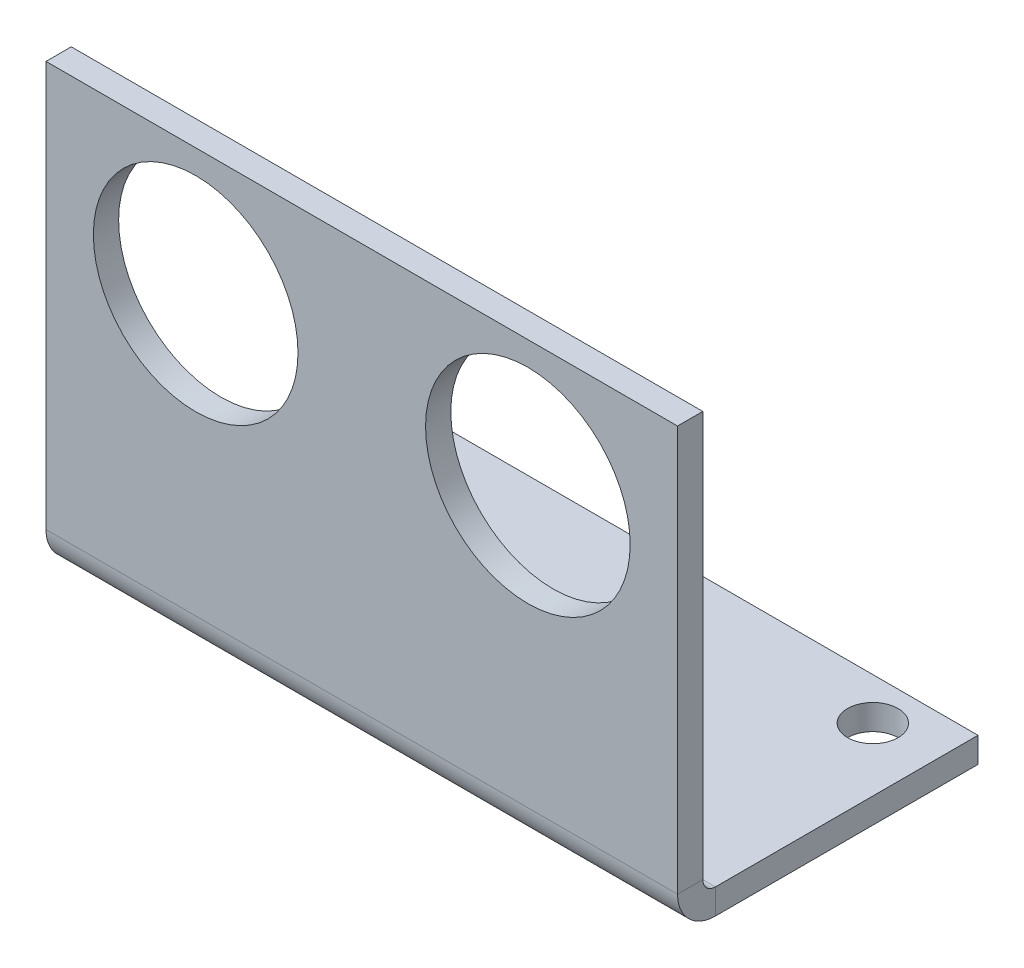
SolidWorks part; units mm, degrees
ref_plane "Front Plane" through (0, 0, 0) normal (0, 0, 1) x (1, 0, 0)
ref_plane "Top Plane" through (0, 0, 0) normal (0, 1, 0) x (1, 0, 0)
ref_plane "Right Plane" through (0, 0, 0) normal (1, 0, 0) x (0, 0, -1)
sketch "Sketch1" plane through (0, 0, 0) normal (0, 0, 1) x (1, 0, 0)
  line L0 (0, 0) -> (0, 24.744) construction
  line L1 (-25, -15) -> (25, -15)
  line L2 (-25, -15) -> (-25, 15)
  line L3 (-25, 15) -> (25, 15)
  line L4 (25, -15) -> (25, 15)
  line L5 (-25, -15) -> (25, 15) construction
  line L6 (-25, 15) -> (25, -15) construction
  circle A0 centre (13.15, 5) radius 8.1
  circle A1 centre (-13.15, 5) radius 8.1
  point P0 (0, 0)
  dimension "D4" = 16.2
  dimension "D5" = 10
  dimension "D1" = 50
  dimension "D2" = 30
  dimension "D3" = 13.15
extrude "Boss-Extrude1" add sketch "Sketch1" along normal blind 2
sketch "Sketch2" plane through (25, 0, 0) normal (1, 0, 0) x (0, 0, -1)
  line L0 (-0.9136, 1.4687) -> (-1, -15)
  line L2 (-2, -15) -> (0, -15) construction
  line L3 (-1, -15) -> (-1, -17.0995)
  line L4 (1, -19.0995) -> (21.7876, -19.0995)
  arc A0 (-1, -17.0995) -> (1, -19.0995) centre (1, -17.0995) ccw
  dimension "D1" = 2
sketch "Sketch3" plane through (0, -15, 0) normal (0, -1, 0) x (1, 0, 0)
  line L4 (-25, 0) -> (25, 0)
  line L5 (25, 0) -> (25, 2)
  line L6 (25, 2) -> (-25, 2)
  line L7 (-25, 2) -> (-25, 0)
  line L8 (-25, 0) -> (25, 0)
  line L9 (25, 0) -> (25, 2)
  line L10 (25, 2) -> (-25, 2)
  line L11 (-25, 2) -> (-25, 0)
  dimension "D1" = 0
sweep "Sweep1" add profiles "Sketch3" path "Sketch2"
sketch "Sketch5" plane through (0, -18.0995, 0) normal (0, 1, 0) x (1, 0, 0)
  line L0 (0, 1) -> (0, 24.3088) construction
  line L1 (-25, 1) -> (25, 1) construction
  circle A0 centre (-20, 18.4604) radius 2
  circle A1 centre (20, 18.4604) radius 2
  dimension "D1" = 20
extrude "Cut-Extrude1" cut sketch "Sketch5" against normal through all
